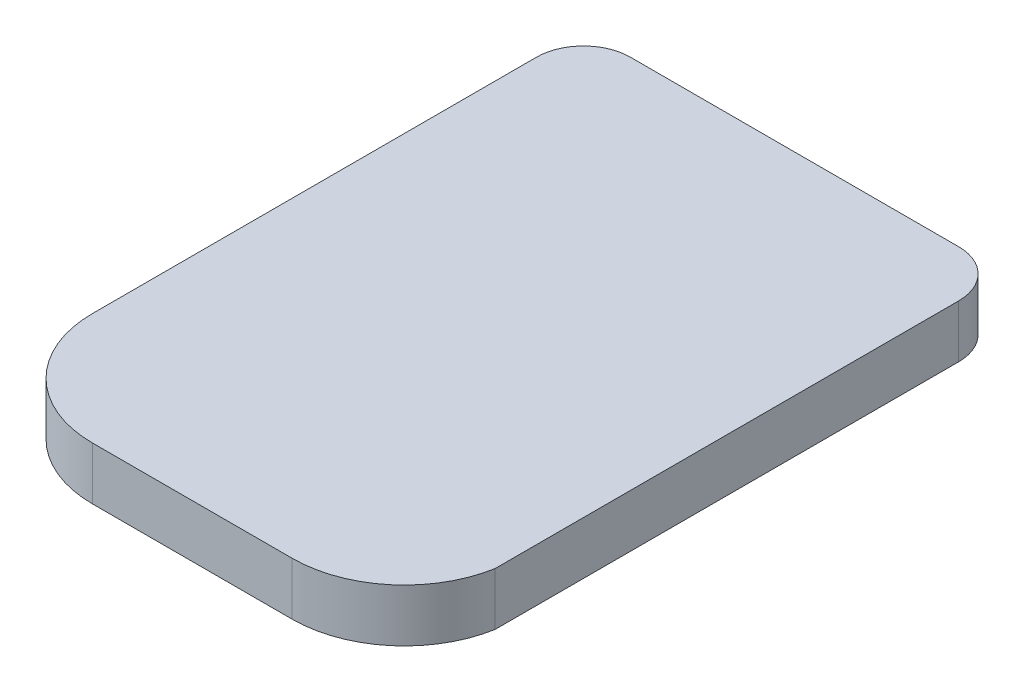
SolidWorks part; units mm, degrees
material "Mahogany"
ref_plane "Front Plane" through (0, 0, 0) normal (0, 0, 1) x (1, 0, 0)
ref_plane "Top Plane" through (0, 0, 0) normal (0, 1, 0) x (1, 0, 0)
ref_plane "Right Plane" through (0, 0, 0) normal (1, 0, 0) x (0, 0, -1)
sketch "Sketch5" plane through (0, 0, 0) normal (0, 1, 0) x (1, 0, 0)
  line L4 (29.8179, 57.072) -> (-32.4121, 57.072) construction
  line L5 (-42.5721, 46.912) -> (-42.5721, -37.2622) construction
  line L6 (-20.0663, -59.768) -> (17.797, -59.768) construction
  line L7 (39.9779, 46.912) -> (39.9779, -41.0722) construction
  line L12 (-41.3021, 46.912) -> (-41.3021, -37.2622)
  line L13 (-20.0663, -58.498) -> (17.797, -58.498)
  line L14 (38.7079, 46.912) -> (38.7079, -40.9623)
  line L15 (29.8179, 55.802) -> (-32.4121, 55.802)
  arc A4 (-32.4121, 57.072) -> (-42.5721, 46.912) centre (-32.4121, 46.912) ccw construction
  arc A5 (-42.5721, -37.2622) -> (-20.0663, -59.768) centre (-20.0663, -37.2622) ccw construction
  arc A6 (17.797, -59.768) -> (39.9779, -41.0722) centre (17.797, -37.2622) ccw construction
  arc A7 (39.9779, 46.912) -> (29.8179, 57.072) centre (29.8179, 46.912) ccw construction
  arc A12 (-41.3021, -37.2622) -> (-20.0663, -58.498) centre (-20.0663, -37.2622) ccw
  arc A13 (17.797, -58.498) -> (38.7079, -40.9623) centre (17.797, -37.2622) ccw
  arc A14 (38.7079, 46.912) -> (29.8179, 55.802) centre (29.8179, 46.912) ccw
  arc A15 (-32.4121, 55.802) -> (-41.3021, 46.912) centre (-32.4121, 46.912) ccw
  dimension "D1" = 10.16
  dimension "D2" = 10.16
  dimension "D3" = 22.5058
  dimension "D4" = 22.5058
  dimension "D5" = 116.84
  dimension "D6" = 82.55
  dimension "D7" = 1.27
extrude "Boss-Extrude6" add sketch "Sketch5" along normal blind 10
